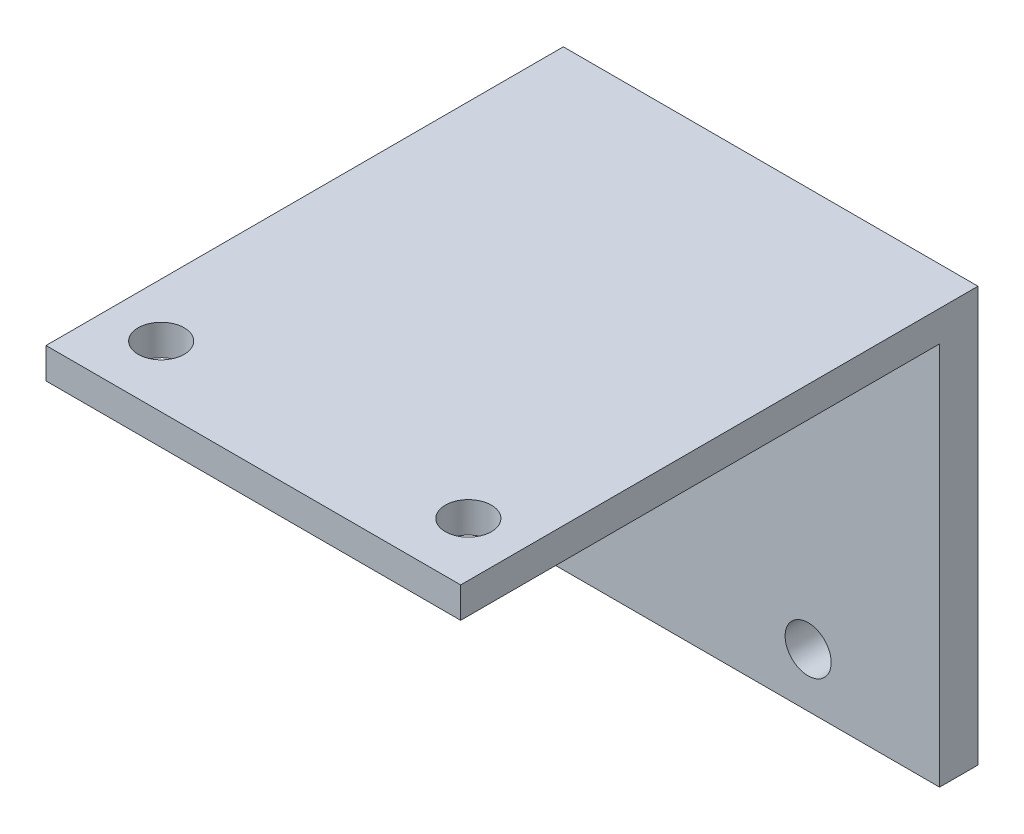
SolidWorks part; units mm, degrees
ref_plane "Plan de face" through (0, 0, 0) normal (0, 0, 1) x (1, 0, 0)
ref_plane "Plan de dessus" through (0, 0, 0) normal (0, 1, 0) x (1, 0, 0)
ref_plane "Plan de droite" through (0, 0, 0) normal (1, 0, 0) x (0, 0, -1)
sketch "Esquisse1" plane through (0, 0, 0) normal (0, 0, 1) x (1, 0, 0)
  line L1 (-27, -27) -> (27, -27)
  line L2 (-27, -27) -> (-27, 27)
  line L3 (-27, 27) -> (27, 27)
  line L4 (27, -27) -> (27, 27)
  line L5 (-27, -27) -> (27, 27) construction
  line L6 (-27, 27) -> (27, -27) construction
  line L7 (9, -27) -> (-9, -27)
  line L8 (9, -27) -> (9, 27)
  line L9 (9, 27) -> (-9, 27)
  line L10 (-9, -27) -> (-9, 27)
  line L11 (9, -27) -> (-9, 27) construction
  line L12 (9, 27) -> (-9, -27) construction
  circle A0 centre (9.88, 20) radius 3
  circle A1 centre (9.88, -20) radius 3
  point P0 (0, 0)
  point P7 (0, 0)
  dimension "D4" = 6
  dimension "D1" = 54
  dimension "D2" = 54
  dimension "D3" = 17.12
  dimension "D5" = 7
  dimension "D7" = 2
extrude "Boss.-Extru.1" add sketch "Esquisse1" along normal blind 67.37 contours L8 L1 L4 L3 | L1 L10 L3 L2 | L10 L1 L8 L3 A1 A0
sketch "Esquisse2" plane through (0, 0, 67.37) normal (0, 0, 1) x (1, 0, 0)
  line L8 (23, 23) -> (-23, 23)
  line L9 (-23, 23) -> (-23, -23)
  line L10 (-23, -23) -> (23, -23)
  line L11 (23, -23) -> (23, 23)
  line L12 (38.775, 23) -> (-47.1129, 23)
  line L13 (-47.1129, 23) -> (-47.1129, -35.7903)
  line L14 (-47.1129, -35.7903) -> (38.775, -35.7903)
  line L15 (38.775, -35.7903) -> (38.775, 23)
  dimension "D1" = 4
extrude "Enlèv. mat.-Extru.1" cut sketch "Esquisse2" against normal blind 62.37
sketch "Esquisse3" plane through (0, 23, 0) normal (0, -1, 0) x (1, 0, 0)
  line L0 (27, 67.37) -> (-27, 67.37) construction
  line L1 (-27, 67.37) -> (-27, 5) construction
  circle A0 centre (-20, 59.37) radius 3
  circle A1 centre (20, 59.37) radius 3
  dimension "D3" = 6
  dimension "D1" = 8
  dimension "D2" = 7
  dimension "D4" = 2
extrude "Enlèv. mat.-Extru.2" cut sketch "Esquisse3" against normal blind 62.37
